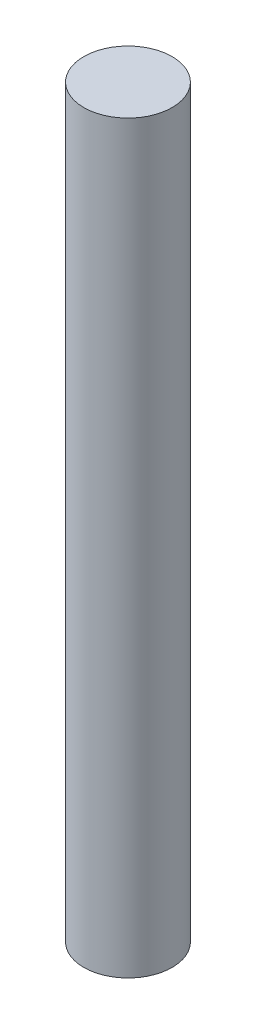
SolidWorks part; units mm, degrees
ref_plane "Front Plane" through (0, 0, 0) normal (0, 0, 1) x (1, 0, 0)
ref_plane "Top Plane" through (0, 0, 0) normal (0, 1, 0) x (1, 0, 0)
ref_plane "Right Plane" through (0, 0, 0) normal (1, 0, 0) x (0, 0, -1)
sketch "Sketch1" plane through (0, 0, 0) normal (0, 1, 0) x (1, 0, 0)
  circle A0 centre (0, 0) radius 8
  dimension "D1" = 16
extrude "Boss-Extrude1" add sketch "Sketch1" along normal blind 134.9
